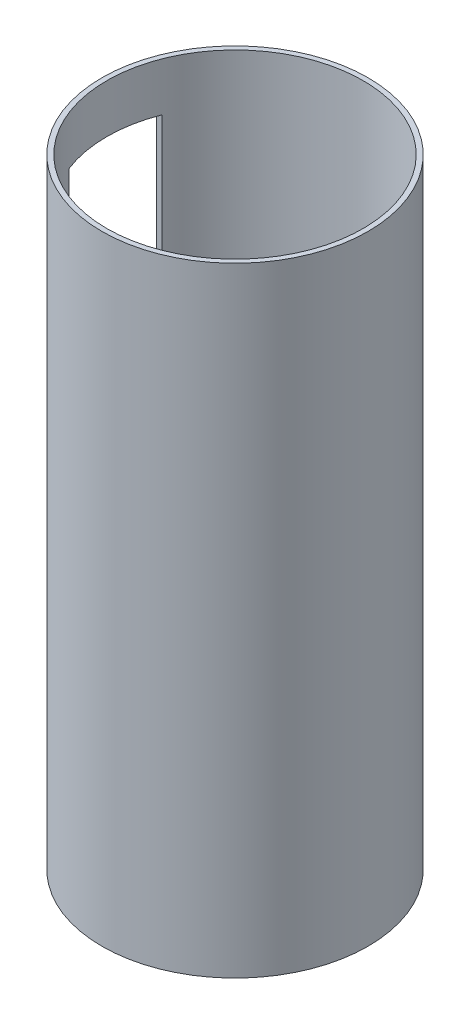
SolidWorks part; units mm, degrees
ref_plane "Front Plane" through (0, 0, 0) normal (0, 0, 1) x (1, 0, 0)
ref_plane "Top Plane" through (0, 0, 0) normal (0, 1, 0) x (1, 0, 0)
ref_plane "Right Plane" through (0, 0, 0) normal (1, 0, 0) x (0, 0, -1)
sketch "Sketch1" plane through (0, 0, 0) normal (0, 1, 0) x (1, 0, 0)
  circle A0 centre (0, 0) radius 20.7
  circle A1 centre (0, 0) radius 21.5
  dimension "D1" = 41.4
  dimension "D2" = 43
extrude "Boss-Extrude1" add sketch "Sketch1" along normal blind 100
sketch "Sketch2" plane through (0, 0, 0) normal (1, 0, 0) x (0, 0, -1)
  line L0 (0, 0) -> (0, 58.4619) construction
  line L2 (-7.5, 92.1622) -> (7.5, 92.1622)
  line L3 (-7.5, 92.1622) -> (-7.5, 52.1622)
  line L4 (-7.5, 52.1622) -> (7.5, 52.1622)
  line L5 (7.5, 92.1622) -> (7.5, 52.1622)
  line L6 (-7.5, 92.1622) -> (7.5, 52.1622) construction
  line L7 (-7.5, 52.1622) -> (7.5, 92.1622) construction
  point P1 (0, 72.1622)
  dimension "D1" = 15
  dimension "D2" = 40
extrude "Cut-Extrude1" cut sketch "Sketch2" against normal blind 100
